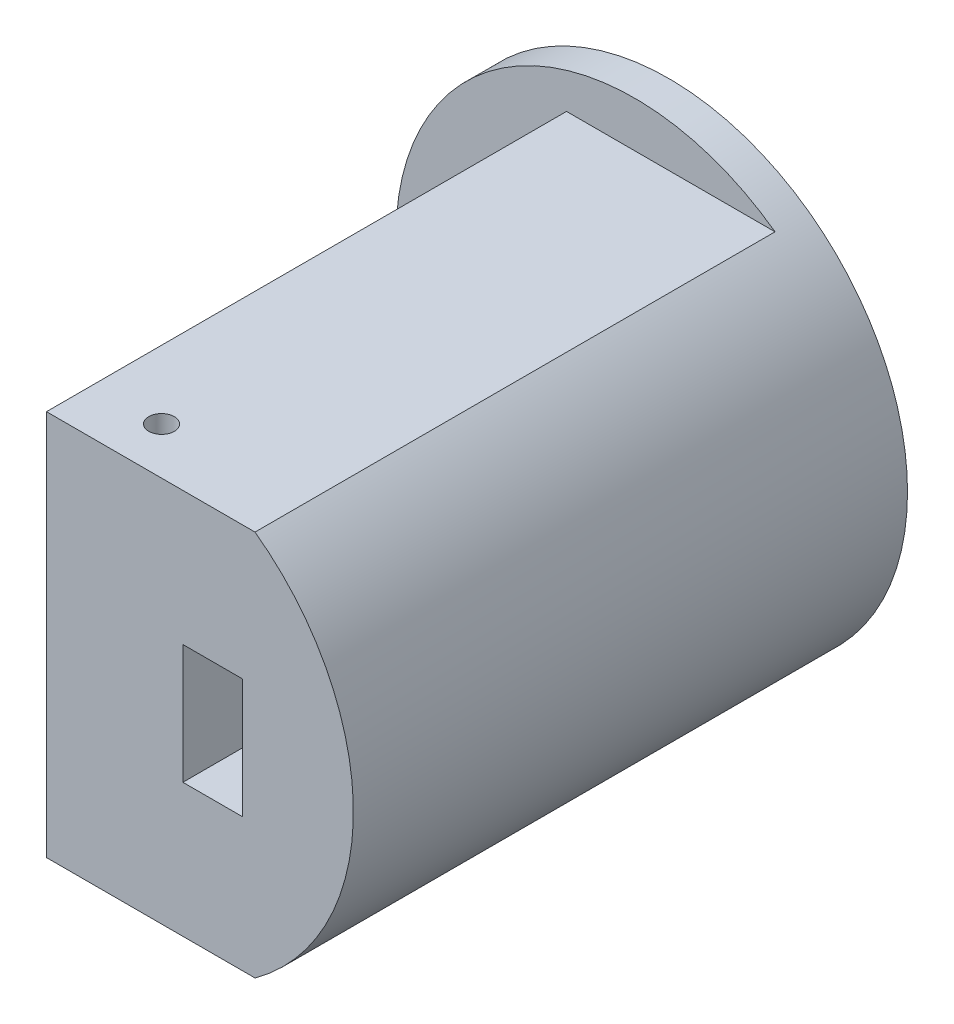
SolidWorks part; units mm, degrees
ref_plane "Front Plane" through (0, 0, 0) normal (0, 0, 1) x (1, 0, 0)
ref_plane "Top Plane" through (0, 0, 0) normal (0, 1, 0) x (1, 0, 0)
ref_plane "Right Plane" through (0, 0, 0) normal (1, 0, 0) x (0, 0, -1)
sketch "Sketch2" plane through (0, 0, 0) normal (0, 0, 1) x (1, 0, 0)
  circle A0 centre (0, 0) radius 14
  dimension "D1" = 28
extrude "Boss-Extrude1" add sketch "Sketch2" along normal blind 2
sketch "Sketch1" plane through (0, 0, 2) normal (0, 0, 1) x (1, 0, 0)
  line L0 (0, 14) -> (0, 11.775) construction
  line L1 (-3, 9.2) -> (3, 9.2)
  line L2 (-3, 9.2) -> (-3, -9.2)
  line L3 (-3, -9.2) -> (3, -9.2)
  line L4 (3, 9.2) -> (3, -9.2)
  line L5 (0, -9.2) -> (0, 9.2) construction
  line L6 (-3, 0) -> (3, 0) construction
  line L7 (-4, -11.325) -> (4, -11.325)
  line L8 (-4, -11.325) -> (-4, 11.325)
  line L9 (-4, 11.325) -> (4, 11.325)
  line L10 (4, -11.325) -> (4, 11.325)
  line L11 (0, 11.325) -> (0, -11.325) construction
  line L12 (-4, 0) -> (4, 0) construction
  line L13 (-2.5, 11.775) -> (2.5, 11.775)
  line L14 (-2.5, 11.775) -> (-2.5, 13.775)
  line L15 (2.5, 11.775) -> (2.5, 13.775)
  circle A0 centre (0, 0) radius 14 construction
  circle A1 centre (0, 0) radius 14
  point P0 (0, 0)
  point P4 (0, 0)
  point P8 (0, 14)
  point P17 (0, 11.775)
  point P21 (-2.5, -13.775)
  dimension "D1" = 6
  dimension "D2" = 18.4
  dimension "D3" = 5
  dimension "D4" = 2
  dimension "D5" = 0.45
  dimension "D6" = 1
  dimension "D7" = 2.45
extrude "Boss-Extrude2" add sketch "Sketch1" along normal blind 25 contours L7 L10 L9 L8 L1 L4 L3 L2 | L15 L13 L14
sketch "Sketch3" plane through (0, 0, 27) normal (0, 0, 1) x (1, 0, 0)
  line L4 (-4, -11.325) -> (4, -11.325)
  line L5 (4, -11.325) -> (4, 11.325)
  line L6 (4, 11.325) -> (-4, 11.325)
  line L7 (-4, 11.325) -> (-4, -11.325)
  line L8 (-4, -11.325) -> (4, -11.325)
  line L9 (4, -11.325) -> (4, 11.325)
  line L10 (4, 11.325) -> (-4, 11.325)
  line L11 (-4, 11.325) -> (-4, -11.325)
  dimension "D1" = 0
extrude "Boss-Extrude3" add sketch "Sketch3" along normal blind 5.5
sketch "Sketch4" plane through (0, 0, 2) normal (0, 0, 1) x (1, 0, 0)
  line L4 (3, -9.2) -> (3, 9.2)
  line L5 (3, 9.2) -> (-3, 9.2)
  line L6 (-3, 9.2) -> (-3, -9.2)
  line L7 (-3, -9.2) -> (3, -9.2)
  line L8 (3, -9.2) -> (3, 9.2)
  line L9 (3, 9.2) -> (-3, 9.2)
  line L10 (-3, 9.2) -> (-3, -9.2)
  line L11 (-3, -9.2) -> (3, -9.2)
  dimension "D1" = 0
extrude "Cut-Extrude1" cut sketch "Sketch4" against normal through all
sketch "Sketch5" plane through (3, 0, 0) normal (-1, 0, 0) x (0, 0, 1)
  line L0 (22, 9.2) -> (22, -9.2)
  line L4 (27, 9.2) -> (0, 9.2)
  line L5 (0, 9.2) -> (0, -9.2)
  line L6 (0, -9.2) -> (27, -9.2)
  line L7 (27, -9.2) -> (27, 9.2)
  line L8 (27, 9.2) -> (0, 9.2)
  line L9 (0, 9.2) -> (0, -9.2)
  line L10 (0, -9.2) -> (27, -9.2)
  line L11 (27, -9.2) -> (27, 9.2)
  line M6 (27, 9.2) -> (0, 9.2)
  line M8 (0, -9.2) -> (27, -9.2)
  line M9 (27, -9.2) -> (27, 9.2)
  dimension "D2" = 5
  dimension "D1" = 0
extrude "Cut-Extrude2" cut sketch "Sketch5" along normal through all contours L0 M6 M8 M9
sketch "Sketch6" plane through (0, 0, 32.5) normal (0, 0, 1) x (1, 0, 0)
  line L4 (-4, 11.325) -> (-4, -11.325)
  line L5 (-4, -11.325) -> (4, -11.325)
  line L6 (4, -11.325) -> (4, 11.325)
  line L7 (4, 11.325) -> (-4, 11.325)
  line L8 (-4, 11.325) -> (-4, -11.325)
  line L9 (-4, -11.325) -> (4, -11.325)
  line L10 (4, -11.325) -> (4, 11.325)
  line L11 (4, 11.325) -> (-4, 11.325)
  dimension "D1" = 0
sketch "Sketch7" plane through (0, 11.325, 0) normal (0, 1, 0) x (1, 0, 0)
  line L0 (-4, -32.5) -> (4, -32.5) construction
  line L1 (-4, -32.5) -> (4, -32.5)
  line L2 (0, -32.5) -> (0, -29.75) construction
  circle A0 centre (0, -29.75) radius 0.75
  dimension "D2" = 1.5
  dimension "D1" = 2.75
extrude "Cut-Extrude3" cut sketch "Sketch7" against normal through all contours A0
sketch "Sketch8" plane through (0, 0, 2) normal (0, 0, 1) x (1, 0, 0)
  line L0 (4, -11.325) -> (4, 11.325) construction
  line L1 (4, -11.325) -> (4, 11.325)
  line L2 (4, 11.325) -> (8.2307, 11.325)
  line L3 (4, -11.325) -> (8.2307, -11.325)
  circle A0 centre (0, 0) radius 14 construction
  circle A1 centre (0, 0) radius 14
  circle M1 centre (0, 0) radius 14
  line M2 (4, 11.325) -> (4, -11.325)
extrude "Boss-Extrude4" add sketch "Sketch8" along normal up to surface (30.5 mm away) contours L3 L2 M2 M1
sketch "Sketch9" plane through (0, 0, 32.5) normal (0, 0, 1) x (1, 0, 0)
  line L0 (4, -11.325) -> (4, 11.325) construction
  line L1 (4, -11.325) -> (4, 11.325)
  line L2 (4, 3.5) -> (4, -3.5)
  line L3 (4, 3.5) -> (7.5, 3.5)
  line L4 (4, -3.5) -> (7.5, -3.5)
  line L5 (7.5, 3.5) -> (7.5, -3.5)
  line L6 (4, -3.5) -> (4, 3.5)
  point P2 (4, 0)
  point P3 (4, -3.5)
  point P4 (4, 3.5)
  point P5 (0, 0)
  point P13 (4, 0)
  dimension "D1" = 7
  dimension "D3" = 3.5
extrude "Cut-Extrude4" cut sketch "Sketch9" against normal blind 6 contours L5 L3 L1 L4
